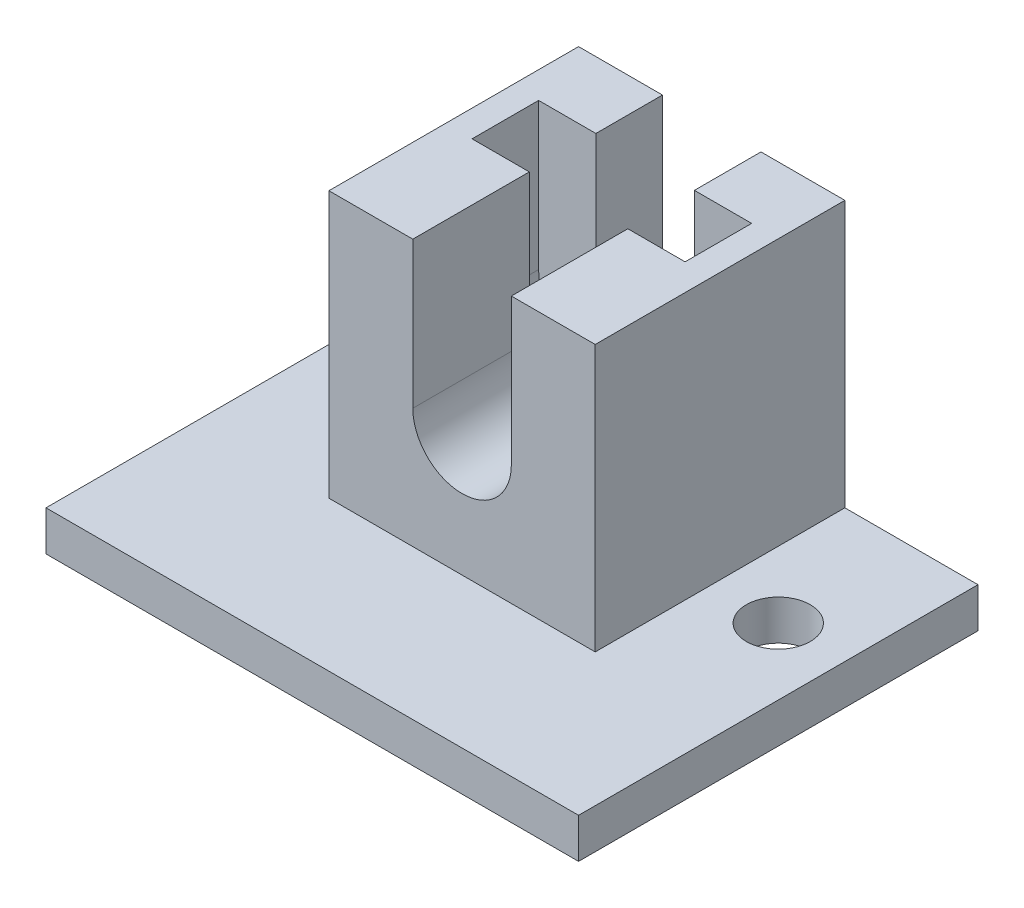
SolidWorks part; units mm, degrees
ref_plane "Plan de face" through (0, 0, 0) normal (0, 0, 1) x (1, 0, 0)
ref_plane "Plan de dessus" through (0, 0, 0) normal (0, 1, 0) x (1, 0, 0)
ref_plane "Plan de droite" through (0, 0, 0) normal (1, 0, 0) x (0, 0, -1)
sketch "Esquisse3" plane through (0, 0, 0) normal (0, 1, 0) x (1, 0, 0)
  line L0 (-0.0516, 15.6297) -> (-0.0516, -14.3703)
  line L1 (-20.0516, 15.6297) -> (19.9484, 15.6297)
  line L2 (-20.0516, 15.6297) -> (-20.0516, -14.3703)
  line L3 (-20.0516, -14.3703) -> (19.9484, -14.3703)
  line L4 (19.9484, 15.6297) -> (19.9484, -14.3703)
  line L5 (-20.0516, 0.6297) -> (19.9484, 0.6297)
  line L6 (19.9484, 15.6297) -> (19.9484, 5.6297)
  line L7 (19.9484, 5.6297) -> (-20.0516, 5.6297)
  line L8 (-0.0516, 5.6297) -> (-15.0516, 5.6297)
  line L9 (-15.0516, 5.6297) -> (14.9484, 5.6297)
  line L10 (-0.0516, 5.6297) -> (-10.0516, 5.6297)
  line L11 (-10.0516, 5.6297) -> (9.9484, 5.6297)
  line L12 (9.9484, 5.6297) -> (9.9484, -14.3703)
  line L13 (9.9484, -14.3703) -> (-10.0516, -14.3703)
  line L14 (-10.0516, -14.3703) -> (-10.0516, 5.6297)
  line L15 (-10.0516, 15.6297) -> (-10.0516, 5.6297)
  line L16 (9.9484, 5.6297) -> (9.9484, 15.6297)
  circle A0 centre (14.9484, 5.6297) radius 2
  circle A1 centre (-15.0516, 5.6297) radius 2
extrude "Boss.-Extru.1" add sketch "Esquisse3" along normal blind 3 contours L3 L14 L5 L2 | L5 L12 L3 L4 | A1 L9 L15 L1 L2 L7 | A1 L7 L2 L5 L14 L9 | L1 L15 L7 L0 | L9 L16 L1 L0 | A0 L7 L4 L1 L16 L9 | A0 L9 L12 L5 L4 L7 | L12 L5 L0 L3 | L14 L3 L0 L5 | L12 L9 L0 L5 | L14 L5 L0 L7
sketch "Esquisse4" plane through (0, 3, 0) normal (0, 1, 0) x (1, 0, 0)
  line L0 (-20.0516, 0.6297) -> (19.9484, 0.6297)
  line L1 (-20.0516, 15.6297) -> (-20.0516, -14.3703) construction
  line L2 (19.9484, 15.6297) -> (19.9484, -14.3703) construction
  line L3 (19.9484, 0.6297) -> (-0.0516, 15.6297)
  line L4 (-20.0516, 15.6297) -> (19.9484, 15.6297) construction
  line L5 (-0.0516, 15.6297) -> (-0.0516, -14.3703)
  line L6 (-20.0516, -14.3703) -> (19.9484, -14.3703) construction
  line L7 (-0.0516, -14.3703) -> (-20.0516, 0.6297)
  line L8 (-0.0516, 15.6297) -> (-20.0516, 0.6297)
  line L9 (-0.0516, -14.3703) -> (19.9484, 0.6297)
  line L10 (-15.0516, 5.6297) -> (14.9484, 5.6297)
  line L11 (14.9484, 5.6297) -> (14.9484, 15.6297)
  line L12 (-15.0516, 5.6297) -> (-15.0516, 15.6297)
  line L13 (-15.0516, 15.6297) -> (14.9484, 15.6297)
  line L14 (-0.0516, 5.6297) -> (-10.0516, 5.6297)
  line L15 (-0.0516, 5.6297) -> (9.9484, 5.6297)
  line L16 (-10.0516, 5.6297) -> (-10.0516, 15.6297)
  line L17 (-10.0516, 15.6297) -> (9.9484, 15.6297)
  line L18 (-15.0516, 5.6297) -> (-15.0516, -3.1203)
  line L19 (-15.0516, -3.1203) -> (14.9484, -3.1203)
  line L20 (14.9484, -3.1203) -> (14.9484, 5.6297)
  line L21 (-10.0516, 5.6297) -> (-10.0516, -3.1203)
  line L22 (9.9484, 5.6297) -> (9.9484, -3.1203)
  line L23 (9.9484, -3.1203) -> (9.9484, 15.6297)
  line M5 (19.9484, 15.6297) -> (-20.0516, 15.6297)
extrude "Boss.-Extru.2" add sketch "Esquisse4" along normal blind 17 contours L10 L21 L0 L5 | L0 L21 L19 L5 | L22 L0 L5 L19 | L22 L10 L5 L0 | L10 L23 L3 L5 | L16 L10 L5 L8 | L16 L8 M5 | L3 L23 L13
sketch "Esquisse5" plane through (0, 20, 0) normal (0, 1, 0) x (1, 0, 0)
  line L0 (-10.0516, 15.6297) -> (-10.0516, 10.6297)
  line L1 (-10.0516, 15.6297) -> (-10.0516, -3.1203) construction
  line L2 (-10.0516, 10.6297) -> (9.9484, 10.6297)
  line L3 (9.9484, 15.6297) -> (9.9484, -3.1203) construction
  line L4 (9.9484, 10.6297) -> (9.9484, 15.6297)
  line L5 (9.9484, 15.6297) -> (-10.0516, 15.6297)
  line L6 (9.9484, 10.6297) -> (-0.0516, 10.6297)
  line L7 (7.9484, 10.6297) -> (-8.0516, 10.6297)
  line L8 (7.9484, 10.6297) -> (7.9484, 5.6297)
  line L9 (-8.0516, 10.6297) -> (-8.0516, 5.6297)
  line L10 (7.9484, 5.6297) -> (-8.0516, 5.6297)
  point P13 (-0.0516, 10.6297)
ref_plane "Plan1" through (0, 0, -10.6297) normal (0, 0, -1) x (-1, 0, 0)
sketch "Esquisse6" plane through (0, 0, -10.6297) normal (0, 0, -1) x (-1, 0, 0)
  line L0 (-7.9484, 20) -> (8.0516, 20)
  line L2 (-7.9484, 12) -> (-7.9484, 20)
  line L5 (-7.9484, 20) -> (-7.9484, 4)
  line L6 (8.0516, 20) -> (8.0516, 4)
  line L11 (8.0516, 20) -> (-7.9484, 20)
  line L12 (8.0516, 20) -> (8.0516, 12)
  arc A1 (-7.9484, 12) -> (8.0516, 12) centre (0.0516, 12) ccw
extrude "Enlèv. mat.-Extru.1" cut sketch "Esquisse6" against normal blind 5 contours L2 A1 L6 L0
sketch "Esquisse7" plane through (0, 0, -15.6297) normal (0, 0, -1) x (-1, 0, 0)
  line L0 (8.0516, 20) -> (8.0516, 4)
  line L1 (-7.9484, 20) -> (8.0516, 20) construction
  line L2 (8.0516, 4) -> (-7.9484, 4)
  line L3 (-7.9484, 4) -> (-7.9484, 20)
  line L4 (-7.9484, 20) -> (8.0516, 20)
  line L5 (8.0516, 20) -> (-7.9484, 4)
  line L6 (8.0516, 4) -> (-7.9484, 20)
  circle A0 centre (0.0516, 12) radius 3
extrude "Enlèv. mat.-Extru.2" cut sketch "Esquisse7" against normal blind 18.75 contours L6 A0 L5 | L5 A0 L6 | L6 A0 L5 | L5 A0 L6
sketch "Esquisse8" plane through (0, 20, 0) normal (0, 1, 0) x (1, 0, 0)
  line L0 (-10.0516, 15.6297) -> (-10.0516, -3.1203)
  line L1 (-10.0516, -3.1203) -> (9.9484, -3.1203)
  line L2 (9.9484, 15.6297) -> (9.9484, -3.1203) construction
  line L3 (9.9484, 15.6297) -> (9.9484, -3.1203) construction
  line L4 (9.9484, -3.1203) -> (9.9484, 15.6297)
  line L5 (9.9484, 15.6297) -> (-10.0516, 15.6297)
  line L6 (-8.0516, 10.6297) -> (-8.0516, 5.6297)
  line L7 (-8.0516, 5.6297) -> (7.9484, 5.6297)
  line L8 (7.9484, 5.6297) -> (7.9484, 10.6297)
  line L9 (7.9484, 10.6297) -> (-8.0516, 10.6297)
extrude "Boss.-Extru.3" add sketch "Esquisse8" along normal blind 3 contours L5 L0 L1 L4 | L9 L6 L7 L8
sketch "Esquisse9" plane through (0, 0, -15.6297) normal (0, 0, -1) x (-1, 0, 0)
  line L0 (0.0516, 9) -> (0.0516, 12)
  circle A0 centre (0.0516, 12) radius 3 construction
  circle A1 centre (0.0516, 12) radius 3.7
  circle M1 centre (0.0516, 12) radius 3
extrude "Enlèv. mat.-Extru.3" cut sketch "Esquisse9" against normal through all contours A1 M1
sketch "Esquisse10" plane through (0, 3, 0) normal (0, 1, 0) x (1, 0, 0)
  line L0 (14.9484, 7.6297) -> (14.9484, 5.6297)
  circle A0 centre (14.9484, 5.6297) radius 2 construction
  circle A1 centre (14.9484, 5.6297) radius 2.4
  circle A2 centre (-15.0516, 5.6297) radius 2.4
  circle M9 centre (-15.0516, 5.6297) radius 2
  circle M10 centre (14.9484, 5.6297) radius 2
extrude "Enlèv. mat.-Extru.4" cut sketch "Esquisse10" against normal blind 6 contours A2 M9 | A1 M10
sketch "Esquisse12" plane through (0, 23, 0) normal (0, 1, 0) x (1, 0, 0)
  line L0 (-10.0516, 15.6297) -> (-0.0516, 15.6297)
  line L1 (9.9484, 15.6297) -> (-10.0516, 15.6297) construction
  line L2 (-0.0516, 15.6297) -> (-0.0516, 10.6297)
  line L3 (7.9484, 10.6297) -> (-8.0516, 10.6297) construction
  line L4 (-0.0516, 10.6297) -> (3.6484, 10.6297)
  line L5 (-0.0516, 10.6297) -> (-3.7516, 10.6297)
  line L6 (-3.7516, 10.6297) -> (-3.7516, 15.6297)
  line L7 (3.6484, 10.6297) -> (3.6484, 15.6297)
  line L8 (3.6484, 15.6297) -> (-0.0516, 15.6297)
  line L9 (-3.7516, 10.6297) -> (-0.0516, 10.6297)
  line L10 (-3.7516, 10.6297) -> (-3.7516, -3.1203)
  line L11 (-10.0516, -3.1203) -> (9.9484, -3.1203) construction
  line L12 (-3.7516, -3.1203) -> (3.6484, -3.1203)
  line L13 (3.6484, -3.1203) -> (3.6484, 10.6297)
  line M2 (9.9484, 15.6297) -> (-10.0516, 15.6297)
  line M4 (-10.0516, -3.1203) -> (9.9484, -3.1203)
  line M5 (-8.0516, 10.6297) -> (7.9484, 10.6297)
  line M7 (7.9484, 5.6297) -> (-8.0516, 5.6297)
extrude "Enlèv. mat.-Extru.5" cut sketch "Esquisse12" against normal up to next contours L6 L2 M5 M2 | L7 L2 M5 M2 | L13 L10 M4 M7
